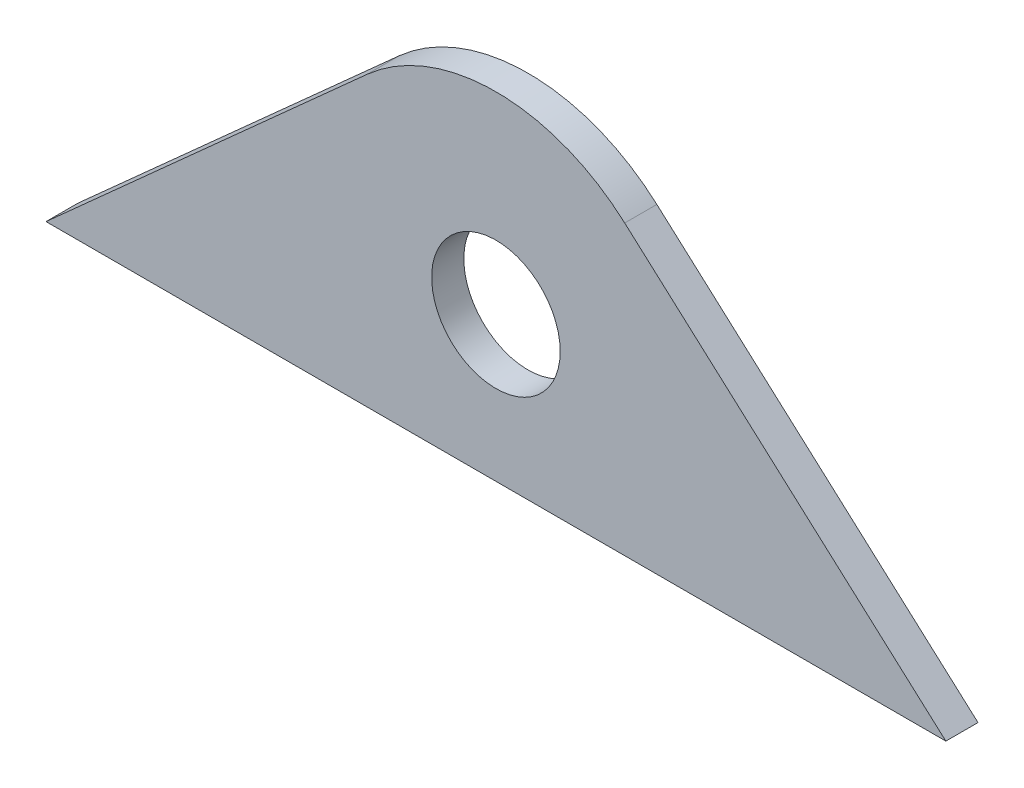
SolidWorks part; units mm, degrees
ref_plane "Front" through (0, 0, 0) normal (0, 0, 1) x (1, 0, 0)
ref_plane "Top" through (0, 0, 0) normal (0, 1, 0) x (1, 0, 0)
ref_plane "Right" through (0, 0, 0) normal (1, 0, 0) x (0, 0, -1)
sketch "Sketch1" plane through (0, 0, 0) normal (0, 0, 1) x (1, 0, 0)
  line L0 (-12.7219, 28.4669) -> (-44.45, 0)
  line L1 (-44.45, 0) -> (44.45, 0)
  line L2 (44.45, 0) -> (12.7219, 28.4669)
  line L3 (0, -50) -> (0, 50) construction
  circle A0 centre (0, 14.2875) radius 6.35
  arc A1 (-12.7219, 28.4669) -> (12.7219, 28.4669) centre (0, 14.2875) cw
  dimension "D2" = 12.7
  dimension "D3" = 19.05
  dimension "D1" = 14.2875
  dimension "D4" = 88.9
extrude "Extrude1" add sketch "Sketch1" along normal blind 3.175
